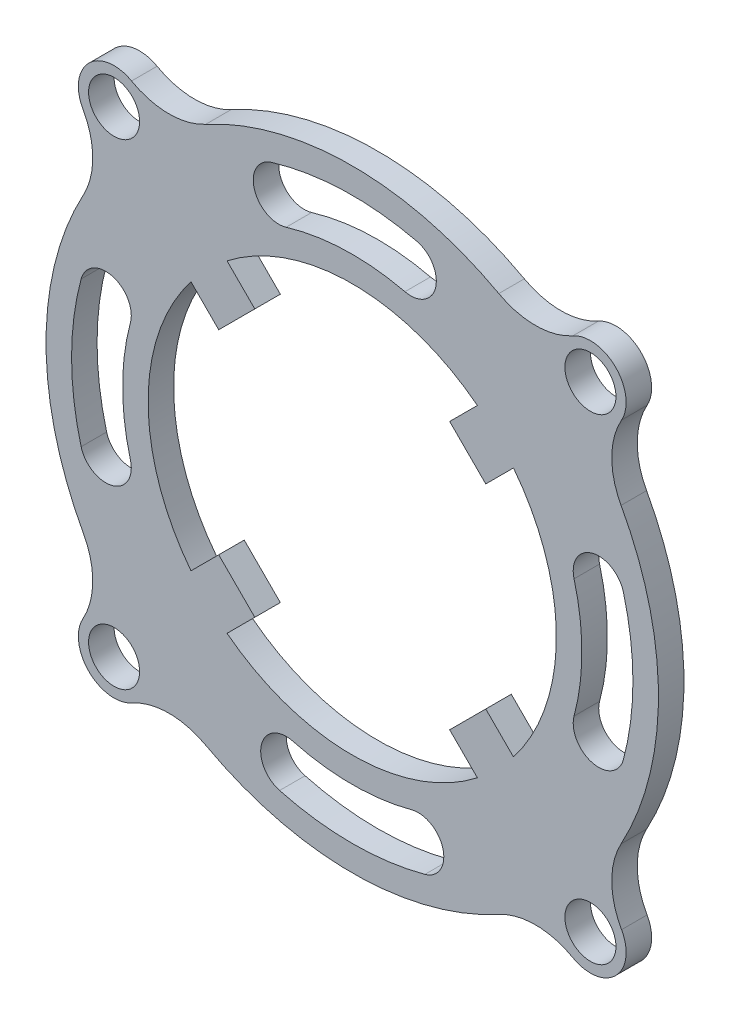
SolidWorks part; units mm, degrees
ref_plane "Plano frontal" through (0, 0, 0) normal (0, 0, 1) x (1, 0, 0)
ref_plane "Plano superior" through (0, 0, 0) normal (0, 1, 0) x (1, 0, 0)
ref_plane "Plano direito" through (0, 0, 0) normal (1, 0, 0) x (0, 0, -1)
sketch "Esboço1" plane through (0, 0, 0) normal (0, 0, 1) x (1, 0, 0)
  circle A3 centre (0, 0) radius 80
  circle A4 centre (0, 0) radius 120
extrude "Ressalto-extrusão1" add sketch "Esboço1" along normal blind 10
sketch "Esboço2" plane through (0, 0, 10) normal (0, 0, 1) x (1, 0, 0)
  line L0 (0, 0) -> (-96.5926, 25.8819) construction
  line L1 (0, 0) -> (-96.5926, -25.8819) construction
  line L2 (0, 0) -> (-25.8819, -96.5926) construction
  line L3 (0, 0) -> (25.8819, -96.5926) construction
  line L4 (0, 0) -> (96.5926, -25.8819) construction
  line L5 (0, 0) -> (96.5926, 25.8819) construction
  line L6 (0, 0) -> (-28.7895, 95.7662) construction
  line L7 (0, 0) -> (22.9506, 97.3307) construction
  arc A6 (22.9506, 97.3307) -> (-28.7895, 95.7662) centre (0, 0) ccw construction
  arc A7 (25.2457, 107.0638) -> (-31.6685, 105.3428) centre (0, 0) ccw
  arc A8 (20.6556, 87.5976) -> (-25.9106, 86.1896) centre (0, 0) ccw
  arc A9 (20.6556, 87.5976) -> (25.2457, 107.0638) centre (22.9506, 97.3307) ccw
  arc A10 (-31.6685, 105.3428) -> (-25.9106, 86.1896) centre (-28.7895, 95.7662) ccw
  arc A17 (-96.5926, 25.8819) -> (-96.5926, -25.8819) centre (0, 0) ccw construction
  arc A21 (96.5926, 25.8819) -> (96.5926, -25.8819) centre (0, 0) cw construction
  arc A22 (106.2518, -28.4701) -> (106.2518, 28.4701) centre (0, 0) ccw
  arc A23 (86.9333, -23.2937) -> (86.9333, 23.2937) centre (0, 0) ccw
  arc A24 (86.9333, -23.2937) -> (106.2518, -28.4701) centre (96.5926, -25.8819) ccw
  arc A25 (106.2518, 28.4701) -> (86.9333, 23.2937) centre (96.5926, 25.8819) ccw
  arc A26 (25.8819, -96.5926) -> (-25.8819, -96.5926) centre (0, 0) cw construction
  arc A27 (-28.4701, -106.2518) -> (28.4701, -106.2518) centre (0, 0) ccw
  arc A28 (-23.2937, -86.9333) -> (23.2937, -86.9333) centre (0, 0) ccw
  arc A29 (-23.2937, -86.9333) -> (-28.4701, -106.2518) centre (-25.8819, -96.5926) ccw
  arc A30 (28.4701, -106.2518) -> (23.2937, -86.9333) centre (25.8819, -96.5926) ccw
  arc A31 (-106.2518, 28.4701) -> (-106.2518, -28.4701) centre (0, 0) ccw
  arc A32 (-86.9333, 23.2937) -> (-86.9333, -23.2937) centre (0, 0) ccw
  arc A33 (-86.9333, 23.2937) -> (-106.2518, 28.4701) centre (-96.5926, 25.8819) ccw
  arc A34 (-106.2518, -28.4701) -> (-86.9333, -23.2937) centre (-96.5926, -25.8819) ccw
  point P6 (-3.0224, 99.9543)
  point P15 (100, 0)
  point P24 (0, -100)
  point P35 (-100, 0)
extrude "Corte-extrusão1" cut sketch "Esboço2" against normal blind 10
sketch "Esboço3" plane through (0, 0, 10) normal (0, 0, 1) x (1, 0, 0)
  line L0 (0, 0) -> (93.3381, 93.3381) construction
  circle A0 centre (93.3381, 93.3381) radius 10
  circle A1 centre (93.3381, 93.3381) radius 14
  circle A5 centre (93.3381, -93.3381) radius 10
  circle A6 centre (93.3381, -93.3381) radius 14
  circle A7 centre (-93.3381, -93.3381) radius 10
  circle A8 centre (-93.3381, -93.3381) radius 14
  circle A9 centre (-93.3381, 93.3381) radius 10
  circle A10 centre (-93.3381, 93.3381) radius 14
  point P18 (0, 0)
  dimension "D1" = 4
extrude "Ressalto-extrusão2" add sketch "Esboço3" against normal blind 10
fillet "Filete1" radius 30 8 edges at (79.8538, -89.5733, 5) (89.5733, -79.8538, 5) (-89.5733, -79.8538, 5) (-79.8538, -89.5733, 5) (-79.8538, 89.5733, 5) (-89.5733, 79.8538, 5) (89.5733, 79.8538, 5) (79.8538, 89.5733, 5)
sketch "Esboço4" plane through (0, 0, 10) normal (0, 0, 1) x (1, 0, 0)
  line L0 (52.3259, -38.1838) -> (38.1838, -52.3259)
  line L3 (38.1838, -52.3259) -> (49.0538, -63.1959)
  line L4 (52.3259, -38.1838) -> (63.1959, -49.0538)
  line L5 (-38.1838, -52.3259) -> (-52.3259, -38.1838)
  line L6 (-52.3259, -38.1838) -> (-63.1959, -49.0538)
  line L7 (38.1838, 52.3259) -> (52.3259, 38.1838)
  line L8 (-38.1838, -52.3259) -> (-49.0538, -63.1959)
  line L10 (52.3259, 38.1838) -> (63.1959, 49.0538)
  line L11 (-52.3259, 38.1838) -> (-38.1838, 52.3259)
  line L12 (38.1838, 52.3259) -> (49.0538, 63.1959)
  line L13 (-38.1838, 52.3259) -> (-49.0538, 63.1959)
  line L14 (-52.3259, 38.1838) -> (-63.1959, 49.0538)
  arc A0 (63.1959, 49.0538) -> (49.0538, 63.1959) centre (0, 0) ccw
  arc A4 (49.0538, -63.1959) -> (63.1959, -49.0538) centre (0, 0) ccw
  arc A5 (-63.1959, -49.0538) -> (-49.0538, -63.1959) centre (0, 0) ccw
  arc A6 (-49.0538, 63.1959) -> (-63.1959, 49.0538) centre (0, 0) ccw
  point P8 (45.2548, -45.2548)
  point P17 (-45.2548, -45.2548)
  point P22 (45.2548, 45.2548)
  point P25 (-45.2548, 45.2548)
  point P26 (0, 0)
  dimension "D1" = 4
extrude "Ressalto-extrusão3" add sketch "Esboço4" against normal blind 10
